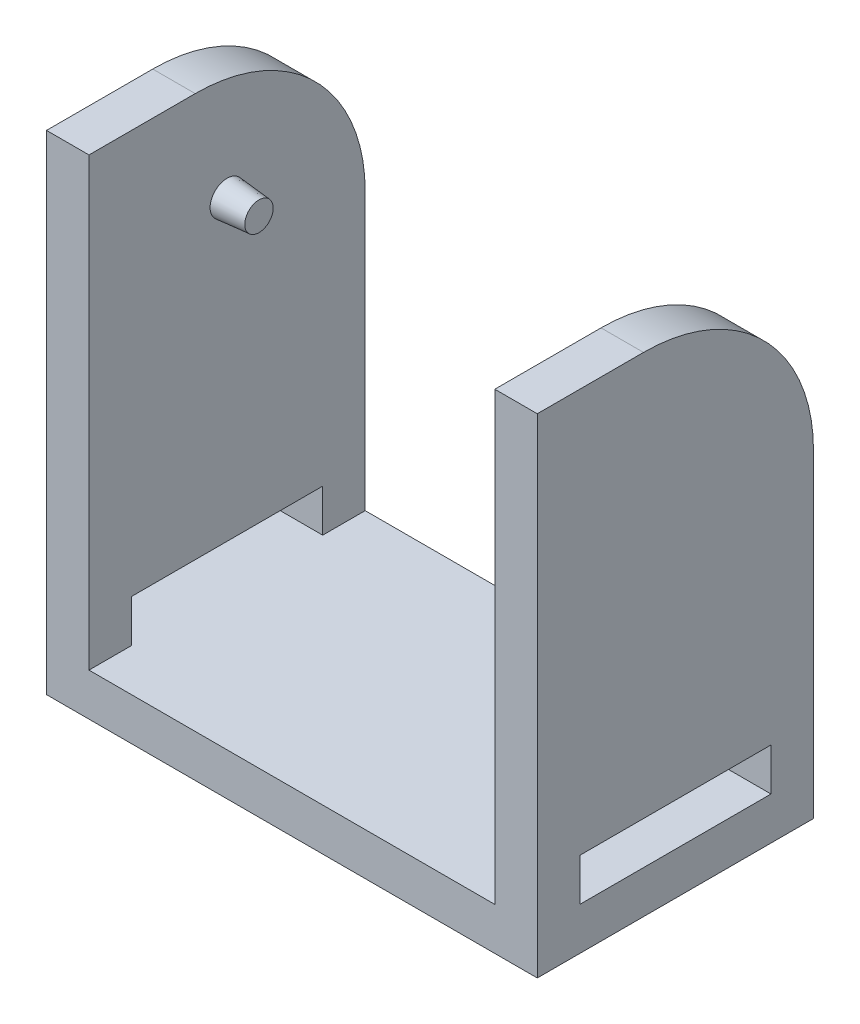
SolidWorks part; units mm, degrees
ref_plane "Спереди" through (0, 0, 0) normal (0, 0, 1) x (1, 0, 0)
ref_plane "Сверху" through (0, 0, 0) normal (0, 1, 0) x (1, 0, 0)
ref_plane "Справа" through (0, 0, 0) normal (1, 0, 0) x (0, 0, -1)
other "Configuration Table"
sketch "Sketch2" plane through (0, 0, 0) normal (0, 1, 0) x (1, 0, 0)
  line L0 (-15.5771, 0) -> (15.5771, 0) construction
  line L2 (9.55, -6.5) -> (-9.55, -6.5)
  line L3 (9.55, -6.5) -> (9.55, 6.5)
  line L4 (9.55, 6.5) -> (-9.55, 6.5)
  line L5 (-9.55, -6.5) -> (-9.55, 6.5)
  line L6 (9.55, -6.5) -> (-9.55, 6.5) construction
  line L7 (9.55, 6.5) -> (-9.55, -6.5) construction
  point P3 (0, 0)
  point P5 (0, 0)
  dimension "D1" = 19.1
  dimension "D2" = 13
extrude "Boss-Extrude1" add sketch "Sketch2" along normal blind 2
sketch "Sketch3" plane through (-9.55, 0, 0) normal (-1, 0, 0) x (0, 0, 1)
  line L0 (6.5, 0) -> (6.5, 23)
  line L1 (0, 0) -> (0, 30.8799) construction
  line L2 (6.5, 23) -> (1.5, 23)
  line L3 (-6.5, 15) -> (-6.5, 0)
  line L4 (-6.5, 0) -> (6.5, 0) construction
  line L5 (-6.5, 2) -> (-6.5, 0) construction
  line L6 (-6.5, 0) -> (6.5, 0)
  circle A0 centre (0, 18) radius 0.8 construction
  arc A1 (1.5, 23) -> (-6.5, 15) centre (1.5, 15) ccw
  dimension "D2" = 18
  dimension "D3" = 8
  dimension "D4" = 1.6
  dimension "D1" = 23
extrude "Boss-Extrude2" add sketch "Sketch3" along normal blind 2
sketch "Sketch4" plane through (-9.55, 0, 0) normal (1, 0, 0) x (0, 0, -1)
  circle A0 centre (0, 18) radius 0.8
  dimension "D1" = 1.6
extrude "Boss-Extrude3" add sketch "Sketch4" along normal blind 1.5 draft 5
sketch "Sketch5" plane through (-9.55, 0, 0) normal (1, 0, 0) x (0, 0, -1)
  line L0 (6.5, 2) -> (-6.5, 2) construction
  line L1 (-4.5, 2) -> (4.5, 2)
  line L2 (-4.5, 2) -> (-4.5, 4)
  line L3 (-4.5, 4) -> (4.5, 4)
  line L4 (4.5, 2) -> (4.5, 4)
  line L7 (0, 0) -> (0, 30.8799) construction
  point P6 (0, 4)
  dimension "D1" = 2
  dimension "D2" = 9
extrude "Cut-Extrude1" cut sketch "Sketch5" against normal up to surface (2 mm away) up to face at (-11.55, 12.5314, -0.0314)
mirror "Mirror1" about plane through (0, 0, 0) normal (1, 0, 0) of "Cut-Extrude1", "Boss-Extrude3", "Boss-Extrude2"
